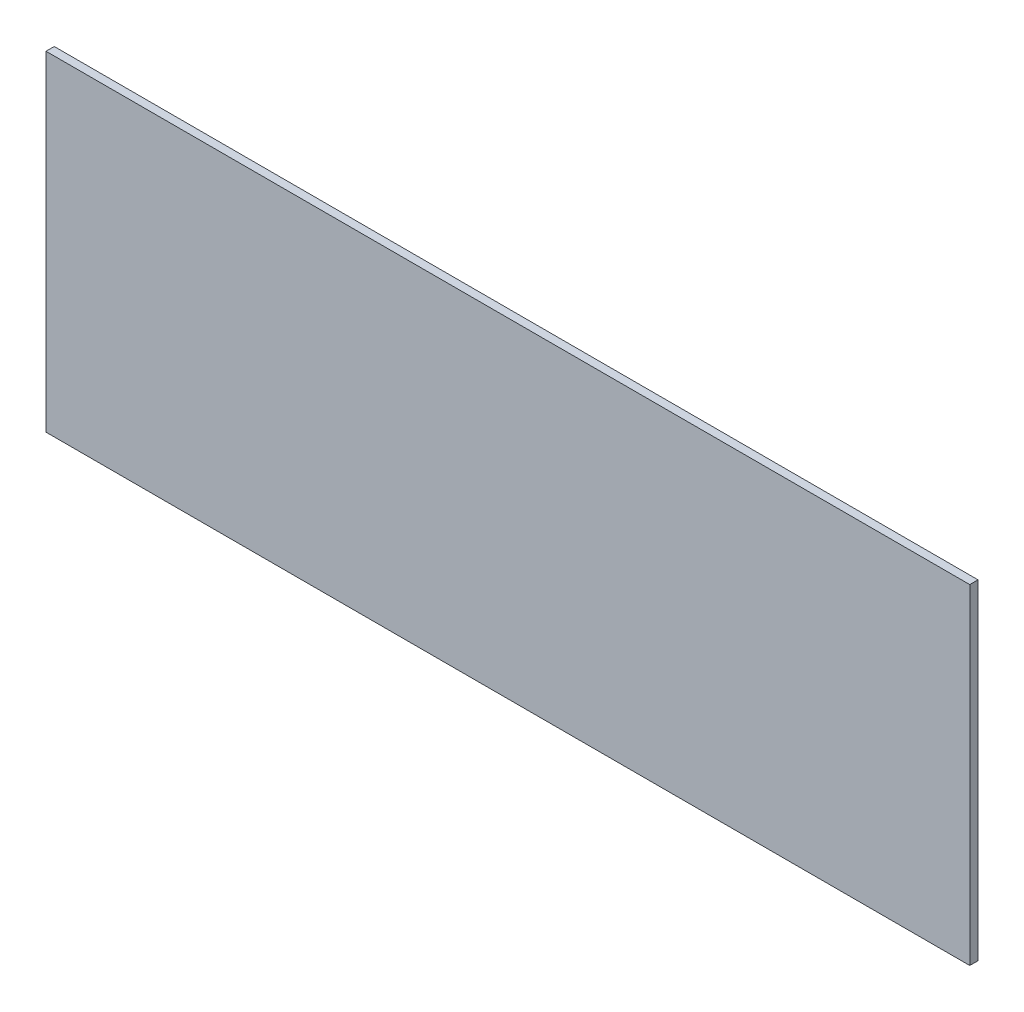
SolidWorks part; units mm, degrees
material "Acrilico (impatto medio-alto)"
ref_plane "Piano frontale" through (0, 0, 0) normal (0, 0, 1) x (1, 0, 0)
ref_plane "Piano superiore" through (0, 0, 0) normal (0, 1, 0) x (1, 0, 0)
ref_plane "Piano destro" through (0, 0, 0) normal (1, 0, 0) x (0, 0, -1)
sketch "Schizzo1" plane through (0, 0, 0) normal (0, 0, 1) x (1, 0, 0)
  line L1 (0, 0) -> (280, 0)
  line L3 (0, 100) -> (280, 100)
  line L14 (0, 0) -> (0, 100)
  line L15 (280, 0) -> (280, 100)
  point P5 (0, 150)
  point P6 (-1.5668, 0)
  point P7 (278.4607, 0)
  point P8 (280, 1.5462)
  dimension "D1" = 100
  dimension "D2" = 280
extrude "Estrusione-Estrusione1" add sketch "Schizzo1" along normal blind 2.5
